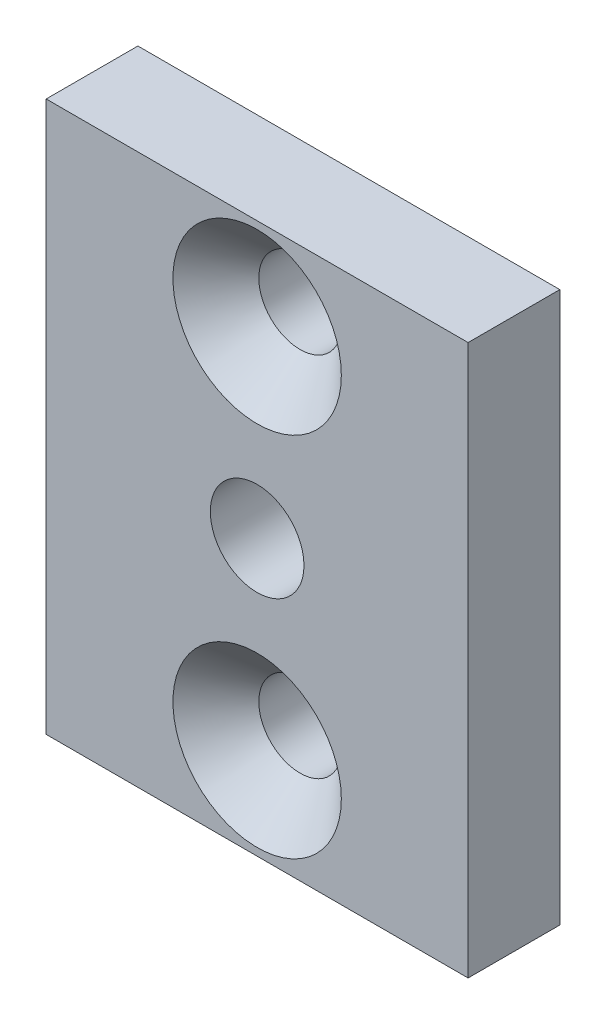
SolidWorks part; units mm, degrees
ref_plane "Ebene vorne" through (0, 0, 0) normal (0, 0, 1) x (1, 0, 0)
ref_plane "Ebene oben" through (0, 0, 0) normal (0, 1, 0) x (1, 0, 0)
ref_plane "Ebene rechts" through (0, 0, 0) normal (1, 0, 0) x (0, 0, -1)
sketch "Skizze1" plane through (0, 0, 0) normal (0, 0, 1) x (1, 0, 0)
  line L1 (0, 0) -> (23, 0)
  line L2 (0, 0) -> (0, 30)
  line L3 (0, 30) -> (23, 30)
  line L4 (23, 0) -> (23, 30)
  dimension "D1" = 23
  dimension "D2" = 30
extrude "Aufsatz-Linear austragen1" add sketch "Skizze1" along normal blind 5
hole_wizard "Formsenkung für M4 Senkschraube mit Innensechskant1" positions "Skizze2" profile "Skizze3" countersink size "M4" standard "DIN" end condition through all
sketch "Skizze2" plane through (0, 0, 5) normal (0, 0, 1) x (1, 0, 0)
  line L0 (0, 30) -> (0, 0) construction
  line L1 (0, 0) -> (23, 0) construction
  line L3 (23, 30) -> (0, 30) construction
  point P0 (11.5, 25)
  point P2 (11.5, 5)
  dimension "D1" = 11.5
  dimension "D2" = 11.5
  dimension "D3" = 5
  dimension "D4" = 5
sketch "Skizze3" plane through (11.5, 25, 5) normal (1, 0, 0) x (0, -1, 0)
  line L0 (0, 0) -> (0, 5)
  line L1 (0, 5) -> (2.25, 5)
  line L2 (2.25, 5) -> (2.25, 2.34)
  line L3 (2.25, 2.34) -> (4.59, 0)
  line L5 (4.59, 0) -> (0, 0)
  line L6 (-2.25, 2.34) -> (-4.59, 0) construction
  line L11 (0, -6.35) -> (0, 107.95) construction
  dimension "Bohrerdurchmesser" = 4.5
  dimension "Bohrungstiefe" = 5
  dimension "Senkdurchmesser (Oben)" = 9.18
  dimension "Senkwinkel (Oben)" = 90
hole_wizard "1/4-20 Gewindebohrung1" positions "Skizze4" profile "Skizze5" tap size "1/4-20" standard "ANSI Inch" end condition through all
sketch "Skizze4" plane through (0, 0, 5) normal (0, 0, 1) x (1, 0, 0)
  line L0 (0, 30) -> (0, 0) construction
  line L1 (0, 0) -> (23, 0) construction
  point P0 (11.5, 15)
  dimension "D1" = 11.5
  dimension "D2" = 15
sketch "Skizze5" plane through (11.5, 15, 5) normal (1, 0, 0) x (0, -1, 0)
  line L0 (0, 0) -> (0, 5)
  line L1 (0, 5) -> (2.5527, 5)
  line L2 (2.5527, 5) -> (2.5527, 0)
  line L5 (2.5527, 0) -> (0, 0)
  line L11 (0, -6.35) -> (0, 107.95) construction
  dimension "Bohrerdurchmesser" = 5.1054
  dimension "Bohrungstiefe" = 5
cosmetic thread "Bohrungsgewinde1" parameters "D2"=6.35
